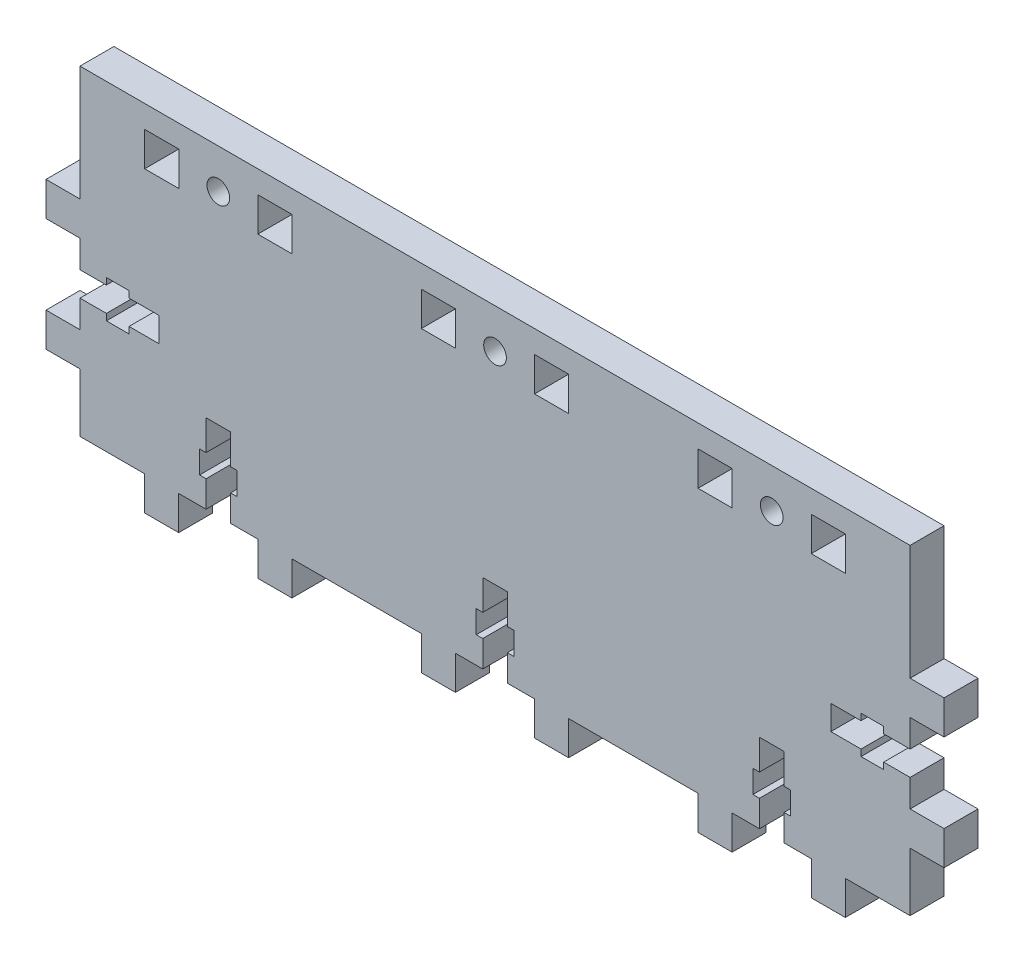
SolidWorks part; units mm, degrees
ref_plane "Front Plane" through (0, 0, 0) normal (0, 0, 1) x (1, 0, 0)
ref_plane "Top Plane" through (0, 0, 0) normal (0, 1, 0) x (1, 0, 0)
ref_plane "Right Plane" through (0, 0, 0) normal (1, 0, 0) x (0, 0, -1)
sketch "Sketch1" plane through (0, 0, 0) normal (0, 0, 1) x (1, 0, 0)
  line L0 (0, 35) -> (110, 35) construction
  line L1 (-110, 70) -> (110, 70) construction
  line L2 (-110, 70) -> (-110, 0)
  line L3 (-110, 0) -> (110, 0)
  line L4 (110, 70) -> (110, 0)
  line L5 (-110, 70) -> (110, 0) construction
  line L6 (-110, 0) -> (110, 70) construction
  line L7 (0, 35) -> (0, 0) construction
  line L8 (-110, 70) -> (-110, 85)
  line L9 (-110, 85) -> (110, 85)
  line L10 (110, 85) -> (110, 70)
  point P0 (0, 35)
  point P13 (0, 17.5)
  line B0 (0, 74.525) -> (-15, 74.525) construction
  line B1 (0, 79.9951) -> (0, 69.5131) construction
  line B2 (19.525, 79.05) -> (10.475, 79.05)
  line B3 (-19.525, 70) -> (-10.475, 70)
  line B4 (-19.525, 70) -> (-19.525, 79.05)
  line B5 (-19.525, 79.05) -> (-10.475, 79.05)
  line B6 (-10.475, 70) -> (-10.475, 79.05)
  line B7 (-19.525, 70) -> (-10.475, 79.05) construction
  line B8 (-19.525, 79.05) -> (-10.475, 70) construction
  line B9 (10.475, 70) -> (10.475, 79.05)
  line B10 (19.525, 70) -> (10.475, 70)
  line B11 (19.525, 70) -> (19.525, 79.05)
  circle B12 centre (0, 74.525) radius 3
  line B13 (-73.3333, 74.525) -> (-88.3333, 74.525) construction
  line B14 (-73.3333, 79.9951) -> (-73.3333, 69.5131) construction
  line B15 (-53.8083, 79.05) -> (-62.8583, 79.05)
  line B16 (-92.8583, 70) -> (-83.8083, 70)
  line B17 (-92.8583, 70) -> (-92.8583, 79.05)
  line B18 (-92.8583, 79.05) -> (-83.8083, 79.05)
  line B19 (-83.8083, 70) -> (-83.8083, 79.05)
  line B20 (-92.8583, 70) -> (-83.8083, 79.05) construction
  line B21 (-92.8583, 79.05) -> (-83.8083, 70) construction
  line B22 (-62.8583, 70) -> (-62.8583, 79.05)
  line B23 (-53.8083, 70) -> (-62.8583, 70)
  line B24 (-53.8083, 70) -> (-53.8083, 79.05)
  circle B25 centre (-73.3333, 74.525) radius 3
  line B26 (73.3333, 74.525) -> (58.3333, 74.525) construction
  line B27 (73.3333, 79.9951) -> (73.3333, 69.5131) construction
  line B28 (92.8583, 79.05) -> (83.8083, 79.05)
  line B29 (53.8083, 70) -> (62.8583, 70)
  line B30 (53.8083, 70) -> (53.8083, 79.05)
  line B31 (53.8083, 79.05) -> (62.8583, 79.05)
  line B32 (62.8583, 70) -> (62.8583, 79.05)
  line B33 (53.8083, 70) -> (62.8583, 79.05) construction
  line B34 (53.8083, 79.05) -> (62.8583, 70) construction
  line B35 (83.8083, 70) -> (83.8083, 79.05)
  line B36 (92.8583, 70) -> (83.8083, 70)
  line B37 (92.8583, 70) -> (92.8583, 79.05)
  circle B38 centre (73.3333, 74.525) radius 3
  line B39 (-19.5, 0) -> (-19.5, -9)
  line B40 (-19.5, -9) -> (-10.5, -9)
  line B41 (-10.5, -9) -> (-10.5, 0)
  line B42 (-10.5, 0) -> (-3.25, 0)
  line B43 (-3.25, 0) -> (-3.25, 7)
  line B44 (-3.25, 7) -> (-4.975, 7)
  line B45 (-4.975, 7) -> (-4.975, 13)
  line B46 (-4.975, 13) -> (-3.25, 13)
  line B47 (-3.25, 13) -> (-3.25, 21)
  line B48 (-3.25, 21) -> (3.25, 21)
  line B49 (0, 21) -> (0, 0) construction
  line B50 (3.25, 13) -> (3.25, 21)
  line B51 (4.975, 13) -> (3.25, 13)
  line B52 (4.975, 7) -> (4.975, 13)
  line B53 (3.25, 7) -> (4.975, 7)
  line B54 (3.25, 0) -> (3.25, 7)
  line B55 (10.5, 0) -> (3.25, 0)
  line B56 (10.5, -9) -> (10.5, 0)
  line B57 (19.5, -9) -> (10.5, -9)
  line B58 (19.5, 0) -> (19.5, -9)
  line B59 (-92.8333, 0) -> (-92.8333, -9)
  line B60 (-92.8333, -9) -> (-83.8333, -9)
  line B61 (-83.8333, -9) -> (-83.8333, 0)
  line B62 (-83.8333, 0) -> (-76.5833, 0)
  line B63 (-76.5833, 0) -> (-76.5833, 7)
  line B64 (-76.5833, 7) -> (-78.3083, 7)
  line B65 (-78.3083, 7) -> (-78.3083, 13)
  line B66 (-78.3083, 13) -> (-76.5833, 13)
  line B67 (-76.5833, 13) -> (-76.5833, 21)
  line B68 (-76.5833, 21) -> (-70.0833, 21)
  line B69 (-73.3333, 21) -> (-73.3333, 0) construction
  line B70 (-70.0833, 13) -> (-70.0833, 21)
  line B71 (-68.3583, 13) -> (-70.0833, 13)
  line B72 (-68.3583, 7) -> (-68.3583, 13)
  line B73 (-70.0833, 7) -> (-68.3583, 7)
  line B74 (-70.0833, 0) -> (-70.0833, 7)
  line B75 (-62.8333, 0) -> (-70.0833, 0)
  line B76 (-62.8333, -9) -> (-62.8333, 0)
  line B77 (-53.8333, -9) -> (-62.8333, -9)
  line B78 (-53.8333, 0) -> (-53.8333, -9)
  line B79 (53.8333, 0) -> (53.8333, -9)
  line B80 (53.8333, -9) -> (62.8333, -9)
  line B81 (62.8333, -9) -> (62.8333, 0)
  line B82 (62.8333, 0) -> (70.0833, 0)
  line B83 (70.0833, 0) -> (70.0833, 7)
  line B84 (70.0833, 7) -> (68.3583, 7)
  line B85 (68.3583, 7) -> (68.3583, 13)
  line B86 (68.3583, 13) -> (70.0833, 13)
  line B87 (70.0833, 13) -> (70.0833, 21)
  line B88 (70.0833, 21) -> (76.5833, 21)
  line B89 (73.3333, 21) -> (73.3333, 0) construction
  line B90 (76.5833, 13) -> (76.5833, 21)
  line B91 (78.3083, 13) -> (76.5833, 13)
  line B92 (78.3083, 7) -> (78.3083, 13)
  line B93 (76.5833, 7) -> (78.3083, 7)
  line B94 (76.5833, 0) -> (76.5833, 7)
  line B95 (83.8333, 0) -> (76.5833, 0)
  line B96 (83.8333, -9) -> (83.8333, 0)
  line B97 (92.8333, -9) -> (83.8333, -9)
  line B98 (92.8333, 0) -> (92.8333, -9)
  line B99 (110, 15.5) -> (119, 15.5)
  line B100 (119, 15.5) -> (119, 24.5)
  line B101 (119, 24.5) -> (110, 24.5)
  line B102 (110, 24.5) -> (110, 31.75)
  line B103 (110, 31.75) -> (103, 31.75)
  line B104 (103, 31.75) -> (103, 30.025)
  line B105 (103, 30.025) -> (97, 30.025)
  line B106 (97, 30.025) -> (97, 31.75)
  line B107 (97, 31.75) -> (89, 31.75)
  line B108 (89, 31.75) -> (89, 38.25)
  line B109 (89, 35) -> (110, 35) construction
  line B110 (97, 38.25) -> (89, 38.25)
  line B111 (97, 39.975) -> (97, 38.25)
  line B112 (103, 39.975) -> (97, 39.975)
  line B113 (103, 38.25) -> (103, 39.975)
  line B114 (110, 38.25) -> (103, 38.25)
  line B115 (110, 45.5) -> (110, 38.25)
  line B116 (119, 45.5) -> (110, 45.5)
  line B117 (119, 54.5) -> (119, 45.5)
  line B118 (110, 54.5) -> (119, 54.5)
  line B119 (-110, 54.5) -> (-119, 54.5)
  line B120 (-119, 54.5) -> (-119, 45.5)
  line B121 (-119, 45.5) -> (-110, 45.5)
  line B122 (-110, 45.5) -> (-110, 38.25)
  line B123 (-110, 38.25) -> (-103, 38.25)
  line B124 (-103, 38.25) -> (-103, 39.975)
  line B125 (-103, 39.975) -> (-97, 39.975)
  line B126 (-97, 39.975) -> (-97, 38.25)
  line B127 (-97, 38.25) -> (-89, 38.25)
  line B128 (-89, 38.25) -> (-89, 31.75)
  line B129 (-89, 35) -> (-110, 35) construction
  line B130 (-97, 31.75) -> (-89, 31.75)
  line B131 (-97, 30.025) -> (-97, 31.75)
  line B132 (-103, 30.025) -> (-97, 30.025)
  line B133 (-103, 31.75) -> (-103, 30.025)
  line B134 (-110, 31.75) -> (-103, 31.75)
  line B135 (-110, 24.5) -> (-110, 31.75)
  line B136 (-119, 24.5) -> (-110, 24.5)
  line B137 (-119, 15.5) -> (-119, 24.5)
  line B138 (-110, 15.5) -> (-119, 15.5)
  dimension "D1" = 70
  dimension "D2" = 220
  dimension "D3" = 36.6667
  dimension "D5" = 15
sketch_block_instance "Insert_9mm_M6_bois-1"
sketch_block "Insert_9mm_M6_bois" parameters "D4"=6, "D1"=9.05, "D2"=9.05, "D3"=15
sketch_block_instance "Insert_9mm_M6_bois-2"
sketch_block_instance "Insert_9mm_M6_bois-3"
sketch_block_instance "Plot_9mm_M6_bois-1"
sketch_block "Plot_9mm_M6_bois" parameters "D1"=9, "D2"=9, "D3"=16, "D4"=30, "D5"=9.95, "D6"=6.5, "D7"=6, "D8"=8
sketch_block_instance "Plot_9mm_M6_bois-2"
sketch_block_instance "Plot_9mm_M6_bois-3"
sketch_block_instance "Plot_9mm_M6_bois-4"
sketch_block_instance "Plot_9mm_M6_bois-6"
extrude "Boss-Extrude2" add sketch "Sketch1" along normal blind 9
